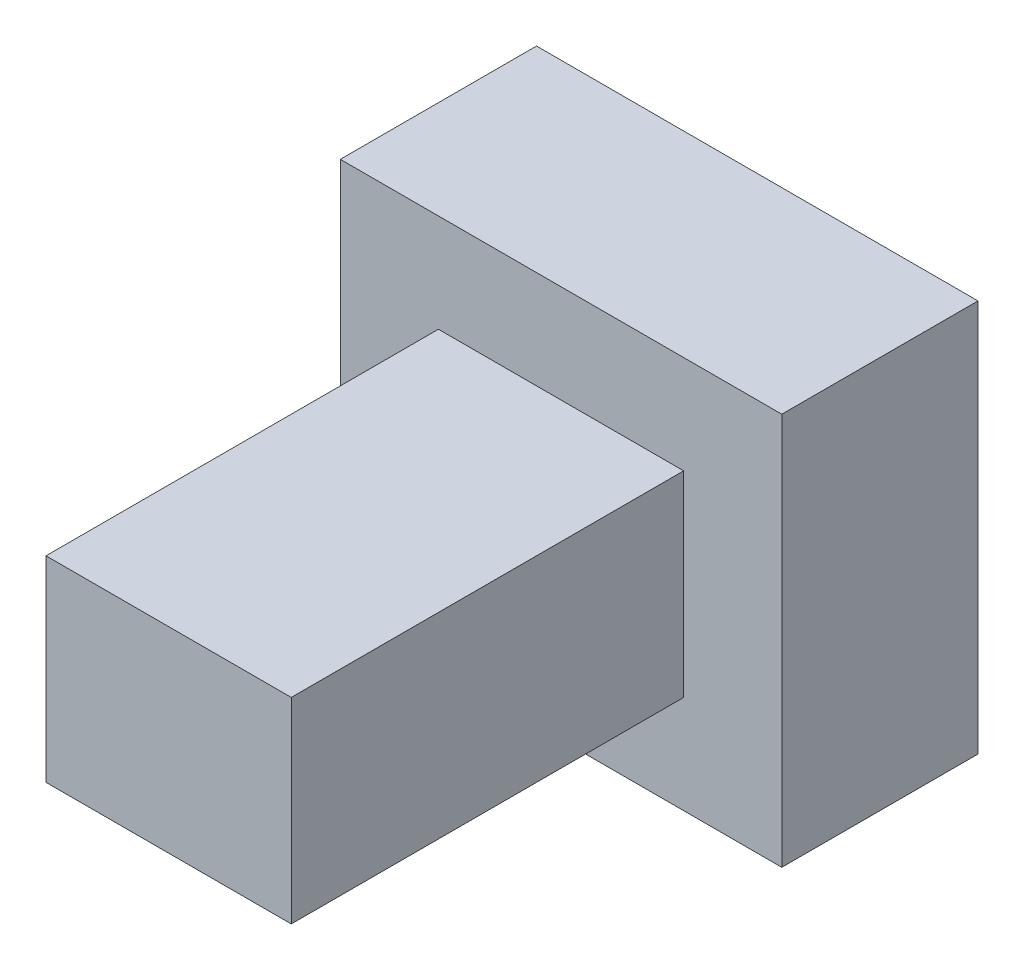
SolidWorks part; units mm, degrees
ref_plane "前视基准面" through (0, 0, 0) normal (0, 0, 1) x (1, 0, 0)
ref_plane "上视基准面" through (0, 0, 0) normal (0, 1, 0) x (1, 0, 0)
ref_plane "右视基准面" through (0, 0, 0) normal (1, 0, 0) x (0, 0, -1)
other "Configuration Table"
sketch "草图1" plane through (0, 0, 0) normal (0, 0, 1) x (1, 0, 0)
  line L1 (0, 0) -> (2.5, 0)
  line L2 (0, 0) -> (0, 2)
  line L3 (0, 2) -> (2.5, 2)
  line L4 (2.5, 0) -> (2.5, 2)
  dimension "D1" = 2.5
  dimension "D2" = 2
extrude "凸台-拉伸1" add sketch "草图1" along normal blind 5
sketch "草图2" plane through (0, 0, 0) normal (0, 0, -1) x (-1, 0, 0)
  line L0 (-3.5, 3) -> (-3.5, -1)
  line L1 (-3.5, -1) -> (1, -1)
  line L2 (1, -1) -> (1, 3)
  line L3 (1, 3) -> (-3.5, 3)
  line L4 (0, 0) -> (0, 2)
  line L5 (0, 2) -> (-2.5, 2)
  line L6 (-2.5, 2) -> (-2.5, 0)
  line L7 (-2.5, 0) -> (0, 0)
  line L8 (0, 0) -> (0, 2)
  line L9 (0, 2) -> (-2.5, 2)
  line L10 (-2.5, 2) -> (-2.5, 0)
  line L11 (-2.5, 0) -> (0, 0)
  dimension "D1" = 0
  dimension "D2" = 1
extrude "凸台-拉伸3" add sketch "草图2" along normal blind 1 and the other way blind 1 contours L0 L1 L2 L3
